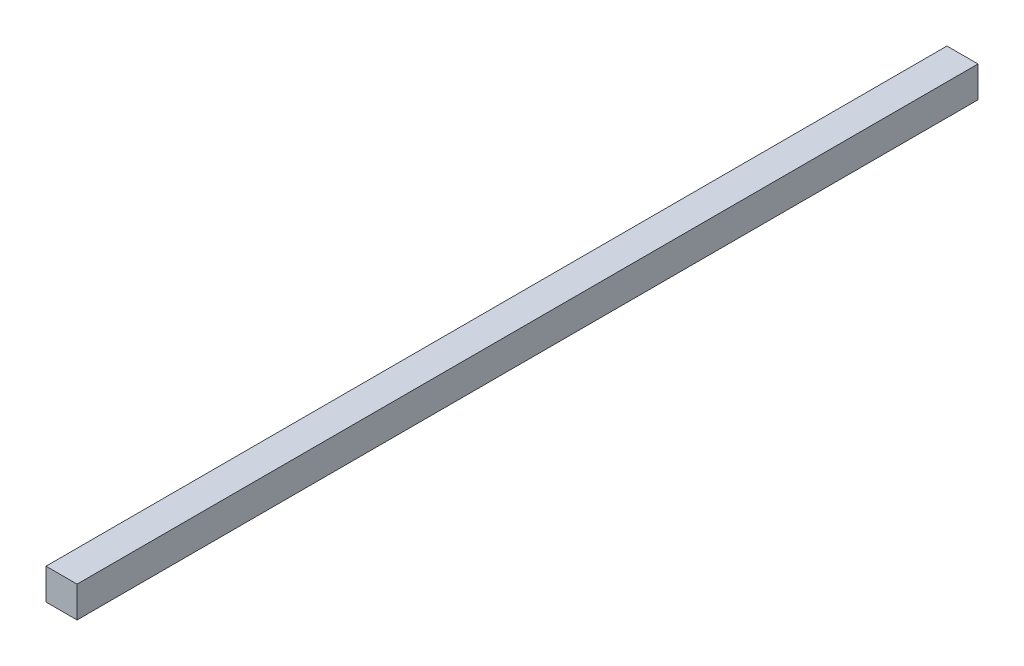
SolidWorks part; units mm, degrees
ref_plane "Спереди" through (0, 0, 0) normal (0, 0, 1) x (1, 0, 0)
ref_plane "Сверху" through (0, 0, 0) normal (0, 1, 0) x (1, 0, 0)
ref_plane "Справа" through (0, 0, 0) normal (1, 0, 0) x (0, 0, -1)
sketch "Эскиз1" plane through (0, 0, 0) normal (0, 0, 1) x (1, 0, 0)
  line L1 (-10, -10) -> (10, -10)
  line L2 (-10, -10) -> (-10, 10)
  line L3 (-10, 10) -> (10, 10)
  line L4 (10, -10) -> (10, 10)
  line L5 (-10, -10) -> (10, 10) construction
  line L6 (-10, 10) -> (10, -10) construction
  point P0 (0, 0)
  dimension "D1" = 20
  dimension "D2" = 20
extrude "Бобышка-Вытянуть1" add sketch "Эскиз1" along normal blind 580
sketch "Эскиз2" plane through (0, 0, 0) normal (0, 0, -1) x (-1, 0, 0)
  circle A0 centre (0, 0) radius 7.5
  dimension "D1" = 15
extrude "Вырез-Вытянуть1" cut sketch "Эскиз2" against normal blind 15
